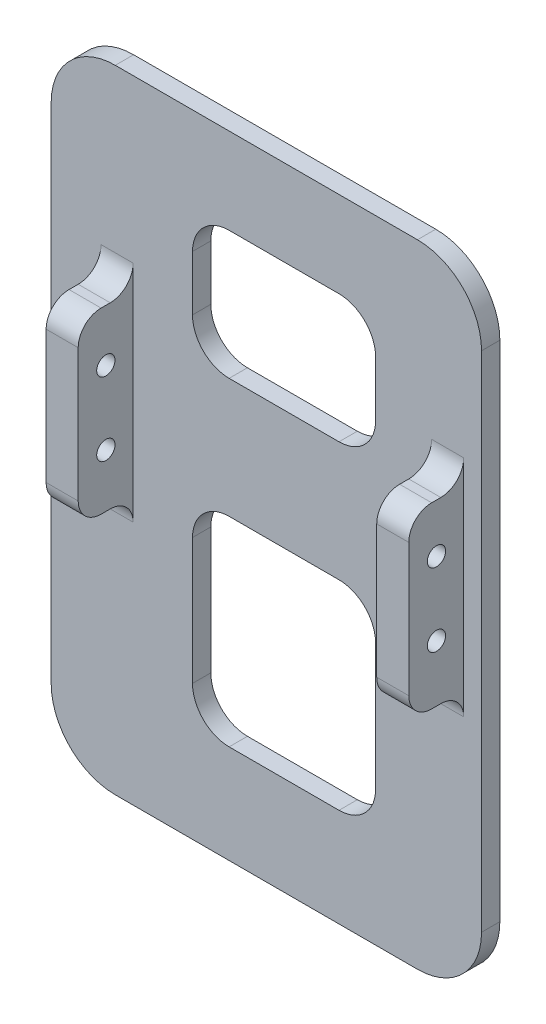
SolidWorks part; units mm, degrees
ref_plane "Front Plane" through (0, 0, 0) normal (0, 0, 1) x (1, 0, 0)
ref_plane "Top Plane" through (0, 0, 0) normal (0, 1, 0) x (1, 0, 0)
ref_plane "Right Plane" through (0, 0, 0) normal (1, 0, 0) x (0, 0, -1)
other "Graphic1"
ref_plane "Plane1" through (0, 0, 10) normal (0, 0, 1) x (1, 0, 0)
sketch "Sketch1" plane through (0, 0, 10) normal (0, 0, 1) x (1, 0, 0)
  line L1 (-263.3567, 441.3983) -> (-216.3567, 441.3983)
  line L2 (-263.3567, 441.3983) -> (-263.3567, 372.3983)
  line L3 (-263.3567, 372.3983) -> (-216.3567, 372.3983)
  line L4 (-216.3567, 441.3983) -> (-216.3567, 372.3983)
  point P4 (-263.1304, 440.4946)
  point P5 (-263.3567, 441.3983)
  dimension "D1" = 47
  dimension "D2" = 69
extrude "Boss-Extrude1" add sketch "Sketch1" along normal blind 2
fillet "Fillet1" radius 7 4 edges at (-263.3567, 441.3983, 11) (-216.3567, 441.3983, 11) (-216.3567, 372.3983, 11) (-263.3567, 372.3983, 11)
sketch "Sketch2" plane through (0, 0, 12) normal (0, 0, 1) x (1, 0, 0)
  line L1 (-247.9236, 432.007) -> (-227.9236, 432.007)
  line L2 (-247.9236, 432.007) -> (-247.9236, 418.007)
  line L3 (-247.9236, 418.007) -> (-227.9236, 418.007)
  line L4 (-227.9236, 432.007) -> (-227.9236, 418.007)
  line L5 (-247.9236, 404.9526) -> (-227.9236, 404.9526)
  line L6 (-247.9236, 404.9526) -> (-247.9236, 383.1526)
  line L7 (-247.9236, 383.1526) -> (-227.9236, 383.1526)
  line L8 (-227.9236, 404.9526) -> (-227.9236, 383.1526)
  point P4 (-247.9236, 432.007)
  point P9 (-247.9236, 404.9526)
  dimension "D1" = 20
  dimension "D2" = 14
  dimension "D3" = 21.8
sketch "Sketch3" plane through (0, 0, 12) normal (0, 0, 1) x (1, 0, 0)
  line L0 (-221.8031, 401.2979) -> (-218.3031, 401.2979)
  line L1 (-254.4077, 421.1619) -> (-257.9077, 421.1619)
  line L2 (-254.4077, 421.1619) -> (-254.4077, 401.6619)
  line L3 (-254.4077, 401.6619) -> (-257.9077, 401.6619)
  line L4 (-257.9077, 421.1619) -> (-257.9077, 401.6619)
  line L7 (-218.3031, 420.7979) -> (-218.3031, 401.2979)
  line L8 (-221.8031, 420.7979) -> (-218.3031, 420.7979)
  line L9 (-221.8031, 420.7979) -> (-221.8031, 401.2979)
  point P5 (-257.9077, 421.1619)
  point P6 (0, 0)
  point P9 (0, 0)
  point P10 (-221.8031, 420.7979)
  point P11 (-218.3031, 402.1382)
  dimension "D1" = 3.5
  dimension "D2" = 19.5
extrude "Cut-Extrude1" cut sketch "Sketch2" against normal blind 2
extrude "Boss-Extrude2" add sketch "Sketch3" along normal blind 6
fillet "Fillet2" radius 4 8 edges at (-227.9236, 383.1526, 11) (-227.9236, 418.007, 11) (-247.9236, 383.1526, 11) (-247.9236, 418.007, 11) (-247.9236, 404.9526, 11) (-247.9236, 432.007, 11) (-227.9236, 404.9526, 11) (-227.9236, 432.007, 11)
fillet "Fillet3" radius 2.5 8 edges at (-220.0531, 420.7979, 12) (-256.1577, 421.1619, 12) (-256.1577, 421.1619, 18) (-220.0531, 420.7979, 18) (-256.1577, 401.6619, 12) (-220.0531, 401.2979, 12) (-220.0531, 401.2979, 18) (-256.1577, 401.6619, 18)
sketch "Sketch4" plane through (-257.9077, 0, 0) normal (-1, 0, 0) x (0, 0, 1)
  circle A0 centre (14.9794, 415.4794) radius 1
  circle A1 centre (14.979, 407.4794) radius 1
  point P4 (0, 0)
  point P5 (14.979, 415.4794)
  dimension "D1" = 8
extrude "Cut-Extrude2" cut sketch "Sketch4" against normal through all
